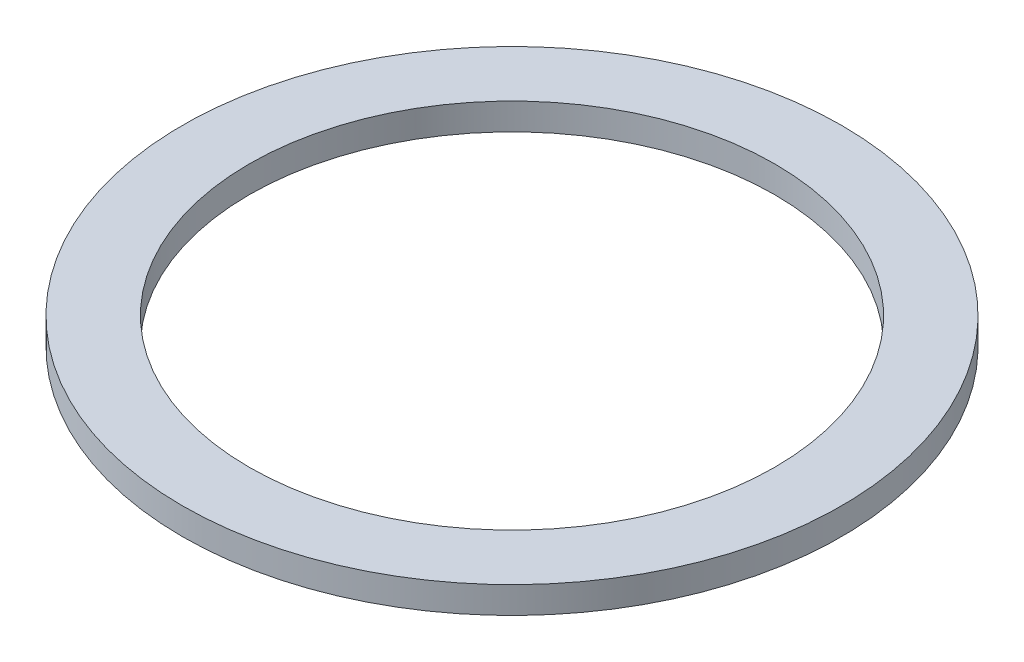
SolidWorks part; units mm, degrees
material "Natural Rubber"
ref_plane "Front Plane" through (0, 0, 0) normal (0, 0, 1) x (1, 0, 0)
ref_plane "Top Plane" through (0, 0, 0) normal (0, 1, 0) x (1, 0, 0)
ref_plane "Right Plane" through (0, 0, 0) normal (1, 0, 0) x (0, 0, -1)
sketch "ProfileS" plane through (0, 0, 0) normal (0, 1, 0) x (1, 0, 0)
  circle A0 centre (0, 0) radius 14.8
  circle A1 centre (0, 0) radius 11.8
  dimension "OD" = 29.6
  dimension "RefID" = 23.6
  dimension "IDControl" = 3
extrude "Profile" add sketch "ProfileS" along normal mid plane 1.2
